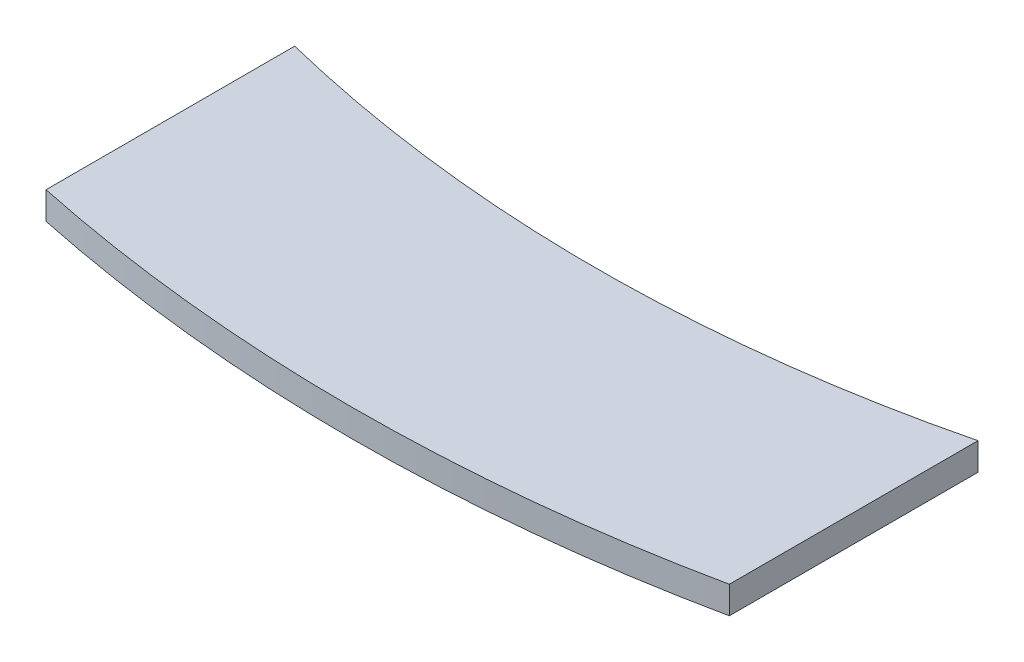
SolidWorks part; units mm, degrees
ref_plane "Front Plane" through (0, 0, 0) normal (0, 0, 1) x (1, 0, 0)
ref_plane "Top Plane" through (0, 0, 0) normal (0, 1, 0) x (1, 0, 0)
ref_plane "Right Plane" through (0, 0, 0) normal (1, 0, 0) x (0, 0, -1)
sketch "Sketch1" plane through (0, 0, 0) normal (0, 1, 0) x (1, 0, 0)
  line L0 (-12.682, 5.2723) -> (-12.682, -3.9579)
  line L1 (12.682, 5.2723) -> (12.682, -3.9579)
  arc A0 (-12.682, 5.2723) -> (12.682, 5.2723) centre (0, 56.5657) ccw
  arc A1 (-12.682, -3.9579) -> (12.682, -3.9579) centre (0, 56.5657) ccw
extrude "Boss-Extrude1" add sketch "Sketch1" along normal blind 1.016
